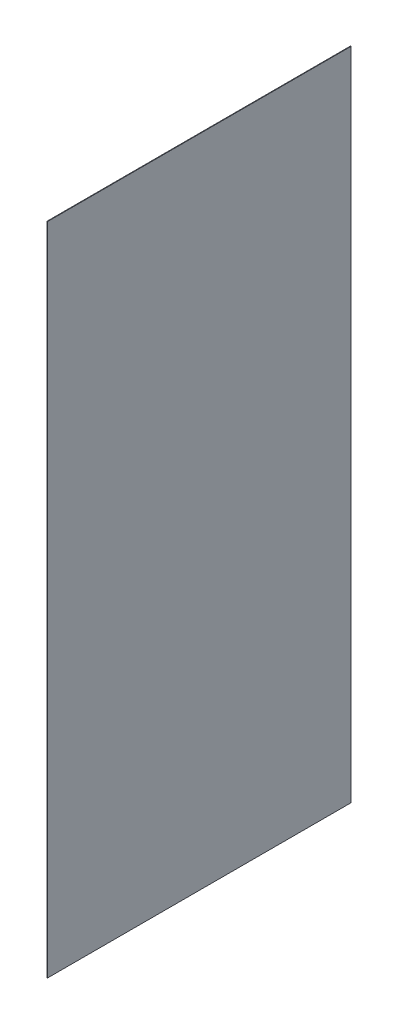
SolidWorks part; units mm, degrees
ref_plane "Front Plane" through (0, 0, 0) normal (0, 0, 1) x (1, 0, 0)
ref_plane "Top Plane" through (0, 0, 0) normal (0, 1, 0) x (1, 0, 0)
ref_plane "Right Plane" through (0, 0, 0) normal (1, 0, 0) x (0, 0, -1)
other "Configuration Table"
sketch "Sketch1" plane through (0, 0, 0) normal (0, 0, 1) x (1, 0, 0)
  line L1 (698.5, 200) -> (700, 200)
  line L2 (698.5, 200) -> (698.5, 1970)
  line L3 (698.5, 1970) -> (700, 1970)
  line L4 (700, 200) -> (700, 1970)
extrude "TOPPING_dis_yan_sag_1" add sketch "Sketch1" against normal blind 820 separate body
